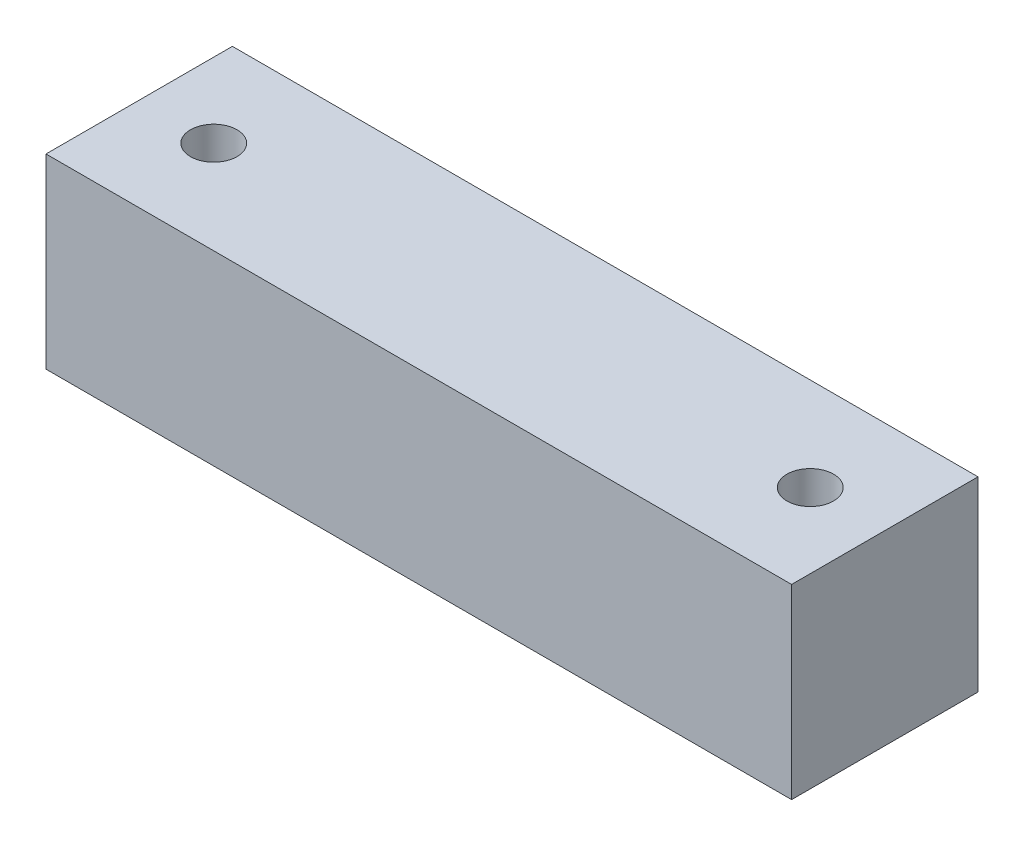
SolidWorks part; units mm, degrees
ref_plane "Front Plane" through (0, 0, 0) normal (0, 0, 1) x (1, 0, 0)
ref_plane "Top Plane" through (0, 0, 0) normal (0, 1, 0) x (1, 0, 0)
ref_plane "Right Plane" through (0, 0, 0) normal (1, 0, 0) x (0, 0, -1)
sketch "Sketch1" plane through (0, 0, 0) normal (0, 0, 1) x (1, 0, 0)
  line L1 (-20, 5) -> (20, 5)
  line L2 (-20, 5) -> (-20, -5)
  line L3 (-20, -5) -> (20, -5)
  line L4 (20, 5) -> (20, -5)
  line L5 (-20, 5) -> (20, -5) construction
  line L6 (-20, -5) -> (20, 5) construction
  point P0 (0, 0)
  dimension "D1" = 40
  dimension "D2" = 10
extrude "Boss-Extrude1" add sketch "Sketch1" along normal blind 10
sketch "Sketch2" plane through (0, -5, 0) normal (0, -1, 0) x (-1, 0, 0)
  line L0 (20, -5) -> (16, -5) construction
  line L1 (20, -10) -> (20, 0) construction
  line L2 (-20, -5) -> (-16, -5) construction
  line L3 (-20, -10) -> (-20, 0) construction
  dimension "D1" = 4
hole_wizard "Tap Drill for M3x0.5 Tap1" positions "Sketch3" profile "Sketch4" hole size "M3x0.5" standard "ANSI Metric" end condition up to next
sketch "Sketch3" plane through (0, -5, 0) normal (0, -1, 0) x (-1, 0, 0)
  point P0 (16, -5)
  point P3 (-16, -5)
sketch "Sketch4" plane through (-16, -5, 5) normal (1, 0, 0) x (0, 0, -1)
  line L0 (0, 0) -> (0, 10)
  line L1 (0, 10) -> (1.25, 10)
  line L2 (1.25, 10) -> (1.25, 0)
  line L5 (1.25, 0) -> (0, 0)
  line L11 (0, -6.35) -> (0, 107.95) construction
  dimension "Thru Hole Dia." = 2.5
  dimension "Thru Hole Depth" = 10
